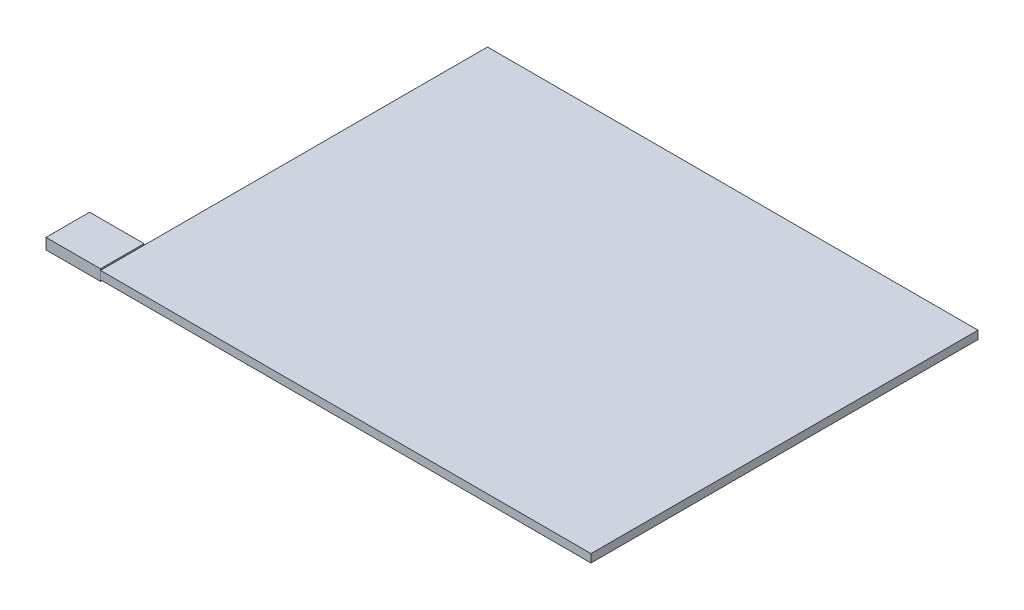
SolidWorks part; units mm, degrees
ref_plane "Front Plane" through (0, 0, 0) normal (0, 0, 1) x (1, 0, 0)
ref_plane "Top Plane" through (0, 0, 0) normal (0, 1, 0) x (1, 0, 0)
ref_plane "Right Plane" through (0, 0, 0) normal (1, 0, 0) x (0, 0, -1)
sketch "Sketch1" plane through (0, 0, 0) normal (0, 1, 0) x (1, 0, 0)
  line L1 (-74, 52.5) -> (74, 52.5)
  line L2 (-74, 52.5) -> (-74, -52.5)
  line L3 (-74, -52.5) -> (74, -52.5)
  line L4 (74, 52.5) -> (74, -52.5)
  line L5 (-74, 52.5) -> (74, -52.5) construction
  line L6 (-74, -52.5) -> (74, 52.5) construction
  point P0 (0, 0)
  dimension "D1" = 105
  dimension "D2" = 148
extrude "Boss-Extrude1" add sketch "Sketch1" along normal mid plane 1.5
sketch "Sketch2" plane through (0, 0, 0) normal (0, 1, 0) x (1, 0, 0)
  line L1 (-74, -52.5) -> (-84, -52.5)
  line L2 (-74, -52.5) -> (-74, -44.5)
  line L3 (-74, -44.5) -> (-84, -44.5)
  line L4 (-84, -52.5) -> (-84, -44.5)
  dimension "D1" = 10
  dimension "D2" = 8
extrude "Boss-Extrude2" add sketch "Sketch2" along normal mid plane 2 separate body
sketch "Sketch3" plane through (0, 0.75, 0) normal (0, 1, 0) x (1, 0, 0)
  line L1 (-74, -52.5) -> (16, -52.5)
  line L2 (-74, -52.5) -> (-74, 18.5)
  line L3 (-74, 18.5) -> (16, 18.5)
  line L4 (74, -52.5) -> (74, 52.5)
  line L5 (74, 52.5) -> (-74, 52.5)
  line L6 (-74, 52.5) -> (-74, -52.5)
  line L7 (-74, -52.5) -> (74, -52.5)
  line L8 (74, -52.5) -> (74, 52.5)
  line L9 (74, 52.5) -> (-74, 52.5)
  line L10 (-74, 52.5) -> (-74, -52.5)
  line L11 (-74, -52.5) -> (74, -52.5)
  line L12 (16, -52.5) -> (16, 18.5)
  line M9 (74, -52.5) -> (74, 52.5)
  line M10 (74, 52.5) -> (-74, 52.5)
  line M11 (-74, 52.5) -> (-74, -52.5)
  line M12 (-74, -52.5) -> (74, -52.5)
  dimension "D2" = 90
  dimension "D3" = 71
  dimension "D1" = 0
extrude "Cut-Extrude1" cut sketch "Sketch3" against normal up to next (1.5 mm away) contours L12 L3 M12 M9 M10 M11
